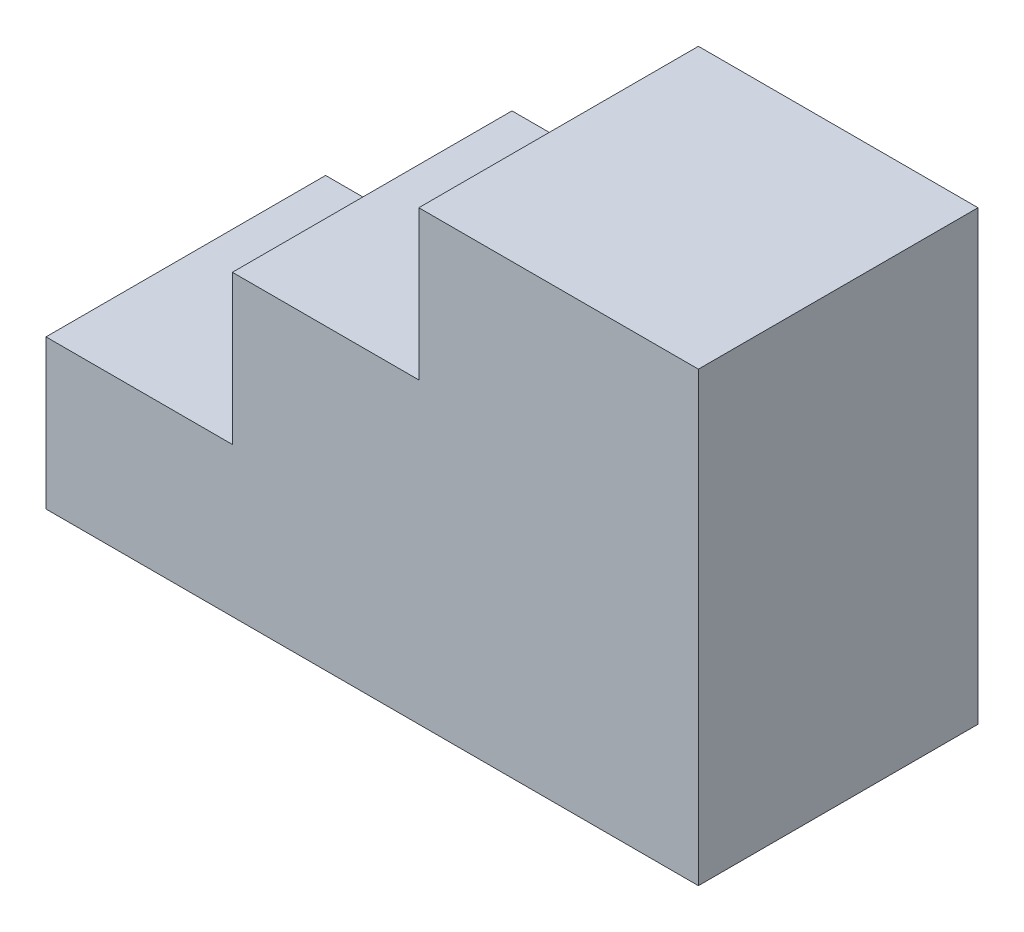
SolidWorks part; units mm, degrees
ref_plane "Alzado" through (0, 0, 0) normal (0, 0, 1) x (1, 0, 0)
ref_plane "Planta" through (0, 0, 0) normal (0, 1, 0) x (1, 0, 0)
ref_plane "Vista lateral" through (0, 0, 0) normal (1, 0, 0) x (0, 0, -1)
sketch "Croquis_perfil_escalera" plane through (0, 0, 0) normal (0, 0, 1) x (1, 0, 0)
  line L0 (-87.5, 0) -> (87.5, 0)
  line L1 (87.5, 0) -> (87.5, 120)
  line L2 (87.5, 120) -> (12.5, 120)
  line L3 (12.5, 120) -> (12.5, 80)
  line L4 (12.5, 80) -> (-37.5, 80)
  line L5 (-37.5, 80) -> (-37.5, 40)
  line L6 (-37.5, 40) -> (-87.5, 40)
  line L7 (-87.5, 40) -> (-87.5, 0)
  dimension "D1" = 50
  dimension "D2" = 175
  dimension "D3" = 40
extrude "Escalera" add sketch "Croquis_perfil_escalera" along normal mid plane 75
sketch "Croquis_agujeros_montaje" plane through (0, 0, 0) normal (0, 1, 0) x (1, 0, 0)
  circle A0 centre (-50, 0) radius 4
  circle A1 centre (50, 0) radius 4
  dimension "D1" = 8
  dimension "D2" = 100
extrude "Agujero_inserto_M6" cut sketch "Croquis_agujeros_montaje" along normal blind 14
